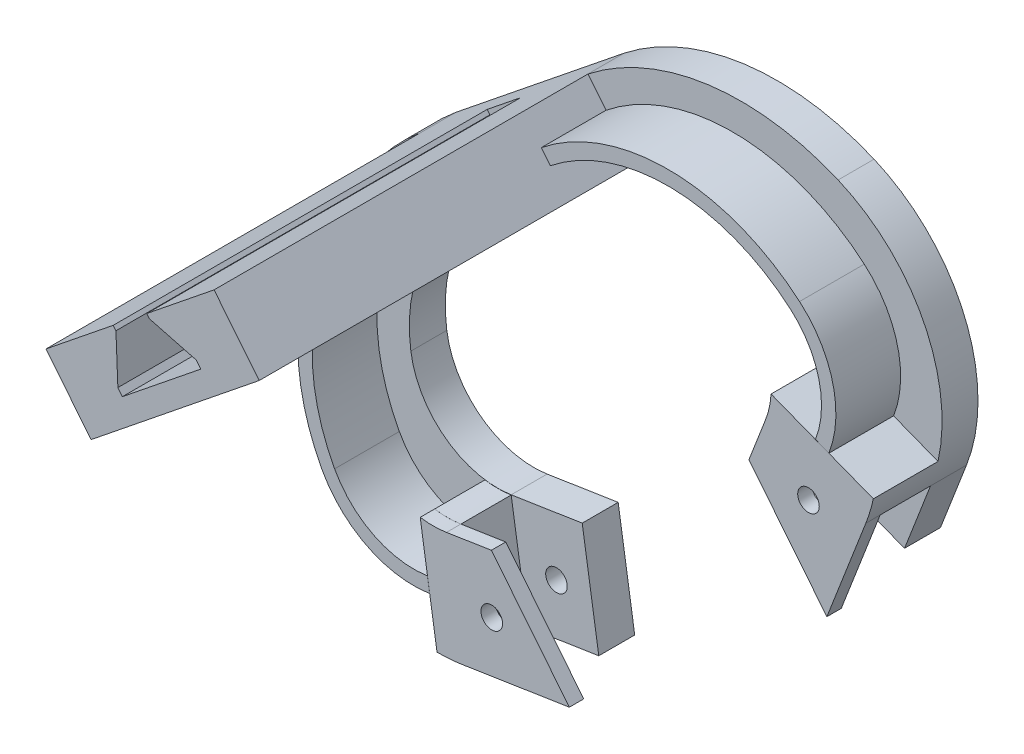
SolidWorks part; units mm, degrees
ref_plane "Piano frontale" through (0, 0, 0) normal (0, 0, 1) x (1, 0, 0)
ref_plane "Piano superiore" through (0, 0, 0) normal (0, 1, 0) x (1, 0, 0)
ref_plane "Piano destro" through (0, 0, 0) normal (1, 0, 0) x (0, 0, -1)
sketch "Schizzo1" plane through (0, 0, 0) normal (0, 0, 1) x (1, 0, 0)
  line L0 (-85.2957, -151.7534) -> (-82.9959, -166.5844) construction
  line L1 (-82.9959, -166.5844) -> (-92.8778, -168.1167)
  line L2 (-85.2957, -151.7534) -> (-95.1776, -153.2857)
  line L3 (-54.4678, -126.9553) -> (-50.8535, -117.6313)
  line L4 (-54.4678, -126.9553) -> (-40.4741, -132.3797)
  line L5 (-85.2957, -151.7534) -> (-82.9959, -166.5844)
  line L6 (-86.4258, -146.4666) -> (-55.0866, -185.4262) construction
  line L7 (-86.4258, -146.4666) -> (-82.5194, -151.3228) construction
  line L8 (-82.5194, -151.3228) -> (-85.2957, -151.7534) construction
  line L9 (-93.6828, -160.6477) -> (-84.1458, -159.1689) construction
  line L10 (-96.0578, -145.3317) -> (-91.3078, -175.9638) construction
  line L11 (-86.4258, -146.4666) -> (-59.3896, -124.7186) construction
  line L12 (-59.3896, -124.7186) -> (-28.0504, -163.6782) construction
  line L13 (-28.0504, -163.6782) -> (-55.0866, -185.4262) construction
  line L14 (-72.9077, -135.5926) -> (-41.5685, -174.5522) construction
  line L15 (-58.4342, -115.0671) -> (-29.5315, -126.2708) construction
  line L16 (-43.9828, -120.669) -> (-47.471, -129.6675) construction
  line L17 (-54.4678, -126.9553) -> (-40.4741, -132.3797) construction
  line L18 (-89.9122, -114.4533) -> (-96.18, -106.6614) construction
  line L19 (-101.6001, -123.8551) -> (-78.2243, -105.0516) construction
  line L20 (-40.4741, -132.3797) -> (-36.8598, -123.0557)
  line L21 (-101.6001, -123.8551) -> (-107.8679, -116.0632) construction
  line L22 (-107.8679, -116.0632) -> (-84.4922, -97.2597) construction
  line L23 (-78.2243, -105.0516) -> (-84.4922, -97.2597) construction
  line L24 (-107.8679, -116.0632) -> (-84.4922, -97.2597)
  line L25 (-101.6001, -123.8551) -> (-78.2243, -105.0516)
  arc A0 (-92.8778, -168.1167) -> (-109.249, -157.2329) centre (-95.4408, -154.2175) cw construction
  arc A1 (-95.1776, -153.2857) -> (-106.6488, -144.6211) centre (-97.8823, -144.9407) cw construction
  arc A2 (-50.8535, -117.6313) -> (-56.8589, -104.5699) centre (-58.4251, -113.2013) ccw construction
  arc A3 (-95.1776, -153.2857) -> (-109.1299, -142.9563) centre (-97.0479, -141.2244) cw
  arc A4 (-36.8598, -123.0557) -> (-43.9828, -104.7326) centre (-49.887, -117.5739) ccw construction
  arc A5 (-92.8778, -168.1167) -> (-119.8406, -149.0462) centre (-96.5147, -144.6629) cw
  arc A6 (-119.8406, -149.0462) -> (-107.8679, -116.0632) centre (-85.9613, -142.6797) cw
  arc A7 (-50.8535, -117.6313) -> (-57.9534, -101.7897) centre (-62.2339, -113.2199) ccw
  arc A8 (-57.9534, -101.7897) -> (-78.2243, -105.0516) centre (-65.2262, -121.2102) ccw
  arc A9 (-109.1299, -142.9563) -> (-101.6001, -123.8551) centre (-88.602, -140.0138) cw
  arc A10 (-36.8598, -123.0557) -> (-49.7097, -92.6327) centre (-58.9895, -114.4775) ccw
  arc A11 (-49.7097, -92.6327) -> (-84.4922, -97.2597) centre (-63.1881, -124.3609) ccw
  dimension "D3" = 30
  dimension "D1" = 10
  dimension "D2" = 10
  dimension "D4" = 15.0083
  dimension "D5" = 10
extrude "Estrusione-Estrusione1" add sketch "Schizzo1" along normal blind 5
sketch "Schizzo2" plane through (0, 0, 5) normal (0, 0, 1) x (1, 0, 0)
  line L1 (-36.8598, -123.0557) -> (-50.8308, -117.6401)
  line L2 (-54.4678, -126.9553) -> (-85.2957, -151.7534) construction
  line L3 (-96.4908, -168.397) -> (-98.8284, -153.3228)
  line L4 (-85.2957, -151.7534) -> (-69.8818, -139.3543) construction
  line L5 (-69.8818, -139.3543) -> (-58.455, -153.5596) construction
  line L6 (-35.8118, -119.5867) -> (-50.035, -114.0733)
  line L7 (-92.8778, -168.1167) -> (-95.1739, -153.3098)
  arc A1 (-95.1739, -153.3098) -> (-109.1299, -142.9563) centre (-97.0443, -141.2482) cw construction
  arc A2 (-36.8598, -123.0557) -> (-49.4205, -92.7579) centre (-58.9895, -114.4775) ccw construction
  arc A3 (-92.8778, -168.1167) -> (-119.7803, -149.3556) centre (-96.5147, -144.6629) cw construction
  arc A4 (-119.8406, -149.0462) -> (-92.8778, -168.1167) centre (-96.5147, -144.6629) ccw construction
  arc A5 (-95.1739, -153.3098) -> (-98.8284, -153.3228) centre (-97.0443, -141.2482) cw
  arc A6 (-92.8778, -168.1167) -> (-96.4908, -168.397) centre (-96.5147, -144.6629) cw
  arc A7 (-50.8308, -117.6401) -> (-57.9534, -101.7897) centre (-62.2115, -113.2286) ccw construction
  arc A8 (-36.8598, -123.0557) -> (-35.8118, -119.5867) centre (-58.9895, -114.4775) ccw
  arc A9 (-50.8308, -117.6401) -> (-50.035, -114.0733) centre (-62.2115, -113.2286) ccw
extrude "Estrusione-Estrusione2" add sketch "Schizzo2" along normal blind 7
sketch "Schizzo3" plane through (0, 0, 12) normal (0, 0, 1) x (1, 0, 0)
  line L0 (-42.2706, -137.0142) -> (-36.8598, -123.0557)
  line L1 (-92.8778, -168.1167) -> (-95.1739, -153.3098) construction
  line L2 (-96.4908, -168.397) -> (-98.8284, -153.3228)
  line L3 (-95.1739, -153.3098) -> (-88.9286, -152.3413)
  line L4 (-98.8284, -153.3228) -> (-50.035, -114.0733) construction
  line L5 (-88.9286, -152.3413) -> (-78.0841, -165.8227)
  line L6 (-78.0841, -165.8227) -> (-92.8778, -168.1167)
  line L7 (-74.4317, -133.6981) -> (-68.2857, -141.3384) construction
  line L8 (-53.115, -123.5328) -> (-42.2706, -137.0142)
  line L9 (-50.8308, -117.6401) -> (-53.115, -123.5328)
  line L10 (-35.8118, -119.5867) -> (-50.035, -114.0733)
  line L11 (-92.3385, -148.1024) -> (-73.9828, -170.9213) construction
  arc A0 (-50.8308, -117.6401) -> (-50.035, -114.0733) centre (-61.3918, -113.4115) ccw
  arc A1 (-92.8778, -168.1167) -> (-96.4908, -168.397) centre (-96.5147, -144.6629) cw
  arc A2 (-36.8598, -123.0557) -> (-35.8118, -119.5867) centre (-58.9895, -114.4775) ccw
  arc A3 (-95.1739, -153.3098) -> (-98.8284, -153.3228) centre (-97.0413, -142.088) cw
extrude "Estrusione-Estrusione3" add sketch "Schizzo3" along normal blind 2
sketch "Schizzo4" plane through (0, 0, 5) normal (0, 0, 1) x (1, 0, 0)
  line L0 (-98.1478, -153.7091) -> (-49.8036, -114.8208) construction
  line L2 (-73.9757, -134.2649) -> (-78.3251, -128.858) construction
  line L3 (-101.6001, -123.8551) -> (-78.2243, -105.0516)
  line L4 (-101.6001, -123.8551) -> (-107.8679, -116.0632)
  line L5 (-107.8679, -116.0632) -> (-84.4922, -97.2597)
  line L6 (-78.2243, -105.0516) -> (-84.4922, -97.2597)
  line L7 (-89.9122, -114.4533) -> (-96.18, -106.6614) construction
  dimension "D1" = 30
  dimension "D2" = 10
extrude "Estrusione-Estrusione4" add sketch "Schizzo4" along normal blind 52
sketch "Schizzo5" plane through (0, 0, 57) normal (0, 0, 1) x (1, 0, 0)
  line L0 (-97.2469, -116.5033) -> (-97.8737, -115.7241)
  line L1 (-100.8552, -110.4221) -> (-89.1673, -101.0204) construction
  line L2 (-84.4922, -97.2597) -> (-107.8679, -116.0632) construction
  line L3 (-107.8679, -116.0632) -> (-101.6001, -123.8551) construction
  line L4 (-101.6001, -123.8551) -> (-78.2243, -105.0516) construction
  line L8 (-98.5176, -108.5418) -> (-93.8425, -104.7811)
  line L9 (-98.5176, -108.5418) -> (-98.1416, -109.0093)
  line L10 (-93.8425, -104.7811) -> (-93.4664, -105.2486)
  line L13 (-86.3382, -107.7283) -> (-86.965, -106.9491)
  line L14 (-98.1416, -109.0093) -> (-97.8737, -115.7241)
  line L15 (-86.965, -106.9491) -> (-93.4664, -105.2486)
  line L16 (-86.3382, -107.7283) -> (-97.2469, -116.5033)
  dimension "D1" = 14
  dimension "D2" = 7
  dimension "D3" = 8
  dimension "D4" = 6
  dimension "D5" = 0.6
  dimension "D6" = 1
extrude "Taglio-Estrusione2" cut sketch "Schizzo5" against normal offset from surface (52 mm away) 5 up to face at (-78.2798, -128.9143, 0)
sketch "Schizzo6" plane through (0, 0, 5) normal (0, 0, 1) x (1, 0, 0)
  line L0 (-98.8284, -153.3228) -> (-96.5147, -168.3971) construction
  line L1 (-107.8679, -116.0632) -> (-101.6001, -123.8551) construction
  line L2 (-101.6001, -123.8551) -> (-78.2243, -105.0516) construction
  line L3 (-84.4922, -97.2597) -> (-78.2243, -105.0516) construction
  line L4 (-81.3582, -101.1556) -> (-104.734, -119.9592) construction
  line L5 (-97.6716, -160.8599) -> (-84.2642, -158.8022) construction
  line L6 (-97.8233, -159.8715) -> (-92.3417, -159.0302) construction
  line L7 (-92.3417, -159.0302) -> (-92.0383, -161.0071) construction
  line L8 (-92.0383, -161.0071) -> (-97.5198, -161.8484) construction
  line L9 (-89.9122, -114.4533) -> (-84.2642, -121.4746) construction
  line L10 (-43.9843, -122.3523) -> (-41.9879, -117.1783) construction
  line L11 (-45.8502, -121.6323) -> (-43.9843, -122.3523) construction
  line L12 (-43.8538, -116.4583) -> (-45.8502, -121.6323) construction
  line L13 (-42.9208, -116.8183) -> (-47.8038, -129.4733) construction
  line L14 (-50.035, -114.0733) -> (-35.8067, -119.5633) construction
  line L15 (-105.3608, -119.18) -> (-104.1072, -120.7383)
  line L16 (-97.5198, -161.8484) -> (-97.8233, -159.8715)
  line L17 (-43.8538, -116.4583) -> (-41.9879, -117.1783)
  line L18 (-81.985, -100.3764) -> (-80.7315, -101.9348)
  arc A0 (-119.8406, -149.0462) -> (-96.4908, -168.397) centre (-96.5147, -144.6629) ccw construction
  arc A1 (-97.6716, -160.8599) -> (-111.6123, -153.9104) centre (-99.7202, -147.5122) cw construction
  arc A2 (-111.6123, -153.9104) -> (-104.734, -119.9592) centre (-87.7506, -141.0723) cw construction
  arc A3 (-46.7217, -101.7122) -> (-81.3582, -101.1556) centre (-64.3748, -122.2687) ccw construction
  arc A4 (-42.9208, -116.8183) -> (-46.7217, -101.7122) centre (-55.5196, -111.9571) ccw construction
  arc A5 (-97.8233, -159.8715) -> (-110.7317, -153.4366) centre (-99.7202, -147.5122) cw
  arc A6 (-110.7317, -153.4366) -> (-104.1072, -120.7383) centre (-87.7506, -141.0723) cw
  arc A7 (-97.5198, -161.8484) -> (-112.493, -154.3842) centre (-99.7202, -147.5122) cw
  arc A8 (-112.493, -154.3842) -> (-105.3608, -119.18) centre (-87.7506, -141.0723) cw
  arc A9 (-46.0702, -100.9535) -> (-81.985, -100.3764) centre (-64.3748, -122.2687) ccw
  arc A10 (-41.9879, -117.1783) -> (-46.0702, -100.9535) centre (-55.5196, -111.9571) ccw
  arc A11 (-47.3732, -102.4708) -> (-80.7315, -101.9348) centre (-64.3748, -122.2687) ccw
  arc A12 (-43.8538, -116.4583) -> (-47.3732, -102.4708) centre (-55.5196, -111.9571) ccw
  point P10 (-97.6716, -160.8599)
  point P11 (-104.734, -119.9592)
  point P13 (-97.8233, -159.8715)
  point P16 (-81.3582, -101.1556)
  point P24 (-97.5198, -161.8484)
  point P30 (-104.1072, -120.7383)
  point P33 (-105.3608, -119.18)
  dimension "D3" = 1
  dimension "D4" = 1
  dimension "D5" = 1
  dimension "D6" = 1
extrude "Estrusione-Estrusione5" add sketch "Schizzo6" along normal blind 9
hole_wizard "Fori filettati Ø3.0mm1" positions "Schizzo8" profile "Schizzo7" hole size "Ø3.0" standard "Ansi Metric" end condition through all
sketch "Schizzo8" plane through (0, 0, 14) normal (0, 0, 1) x (1, 0, 0)
  line L0 (-92.8778, -168.1167) -> (-78.0841, -165.8227) construction
  line L2 (-42.2706, -137.0142) -> (-36.8598, -123.0557) construction
  line L3 (-36.8598, -123.0557) -> (-50.8308, -117.6401) construction
  point P0 (-88.8778, -160.4128)
  point P2 (-88.8778, -160.4128)
  point P4 (-44.8323, -124.2553)
  dimension "D1" = 7
  dimension "D2" = 4
  dimension "D4" = 7
  dimension "D5" = 4
sketch "Schizzo7" plane through (-88.8778, -160.4128, 14) normal (1, 0, 0) x (0, -1, 0)
  line L0 (0, 0) -> (0, 14)
  line L1 (0, 14) -> (1.5, 14)
  line L2 (1.5, 14) -> (1.5, 0)
  line L5 (1.5, 0) -> (0, 0)
  line L11 (0, -6.35) -> (0, 107.95) construction
  dimension "Thru Hole Dia." = 3
  dimension "Thru Hole Depth" = 14
